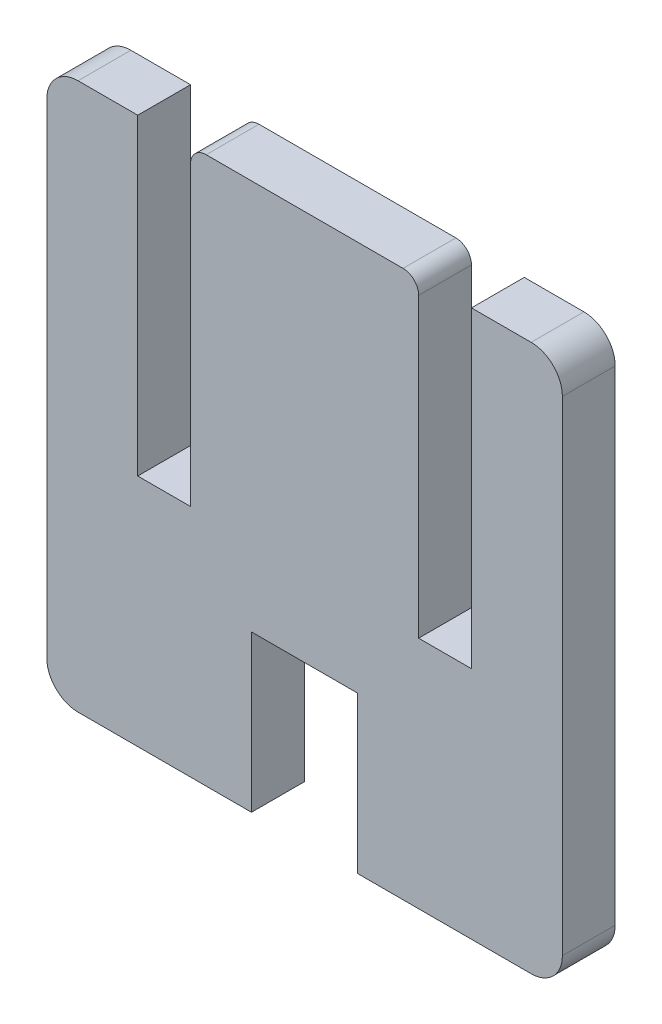
SolidWorks part; units mm, degrees
ref_plane "Front Plane" through (0, 0, 0) normal (0, 0, 1) x (1, 0, 0)
ref_plane "Top Plane" through (0, 0, 0) normal (0, 1, 0) x (1, 0, 0)
ref_plane "Right Plane" through (0, 0, 0) normal (1, 0, 0) x (0, 0, -1)
sketch "Sketch1" plane through (0, 0, 0) normal (0, 0, 1) x (1, 0, 0)
  line L1 (-20.955, -22.225) -> (20.955, -22.225)
  line L2 (-20.955, -22.225) -> (-20.955, 22.225)
  line L3 (-20.955, 22.225) -> (20.955, 22.225)
  line L4 (20.955, -22.225) -> (20.955, 22.225)
  line L5 (-20.955, -22.225) -> (20.955, 22.225) construction
  line L6 (-20.955, 22.225) -> (20.955, -22.225) construction
  point P0 (0, 0)
  dimension "D1" = 44.45
  dimension "D2" = 41.91
extrude "Boss-Extrude1" add sketch "Sketch1" along normal blind 4.2926
fillet "Fillet1" radius 2.54 4 edges at (-20.955, -22.225, 2.1463) (20.955, -22.225, 2.1463) (20.955, 22.225, 2.1463) (-20.955, 22.225, 2.1463)
sketch "Sketch2" plane through (0, 0, 4.2926) normal (0, 0, 1) x (1, 0, 0)
  line L5 (18.415, 22.225) -> (-18.415, 22.225) construction
  line L6 (-18.415, -22.225) -> (18.415, -22.225) construction
  line L7 (-13.5636, 22.225) -> (-9.271, 22.225)
  line L8 (-13.5636, 22.225) -> (-13.5636, -3.175)
  line L9 (-13.5636, -3.175) -> (-9.271, -3.175)
  line L10 (-9.271, 22.225) -> (-9.271, -3.175)
  line L11 (-13.5636, 22.225) -> (-9.271, -3.175) construction
  line L12 (-13.5636, -3.175) -> (-9.271, 22.225) construction
  line L13 (9.271, 22.225) -> (13.5636, 22.225)
  line L14 (9.271, 22.225) -> (9.271, -3.175)
  line L15 (9.271, -3.175) -> (13.5636, -3.175)
  line L16 (13.5636, 22.225) -> (13.5636, -3.175)
  line L17 (9.271, 22.225) -> (13.5636, -3.175) construction
  line L18 (9.271, -3.175) -> (13.5636, 22.225) construction
  line L19 (-11.4173, 9.525) -> (11.4173, 9.525)
  line L20 (-4.318, -22.225) -> (4.318, -22.225)
  line L21 (-4.318, -22.225) -> (-4.318, -9.525)
  line L22 (-4.318, -9.525) -> (4.318, -9.525)
  line L23 (4.318, -22.225) -> (4.318, -9.525)
  line L24 (-4.318, -22.225) -> (4.318, -9.525) construction
  line L25 (-4.318, -9.525) -> (4.318, -22.225) construction
  point P0 (0, 9.525)
  point P4 (0, -15.875)
  point P5 (-11.4173, 9.525)
  point P11 (11.4173, 9.525)
  dimension "D1" = 4.2926
  dimension "D2" = 4.2926
  dimension "D5" = 18.542
  dimension "D3" = 25.4
  dimension "D4" = 8.636
  dimension "D6" = 12.7
extrude "Cut-Extrude2" cut sketch "Sketch2" against normal blind 4.2926
fillet "Fillet3" radius 1.27 2 edges at (9.271, 22.225, 2.1463) (-9.271, 22.225, 2.1463)
equation "\"thick\"=0.169"
equation "\"D1@Boss-Extrude1\"=\"thick\""
equation "\"D1@Sketch2\"=\"thick\""
equation "\"D2@Sketch2\"=\"thick\""
equation "\"2thick\"=0.305913"
equation "\"2xthick\"=0.338"
